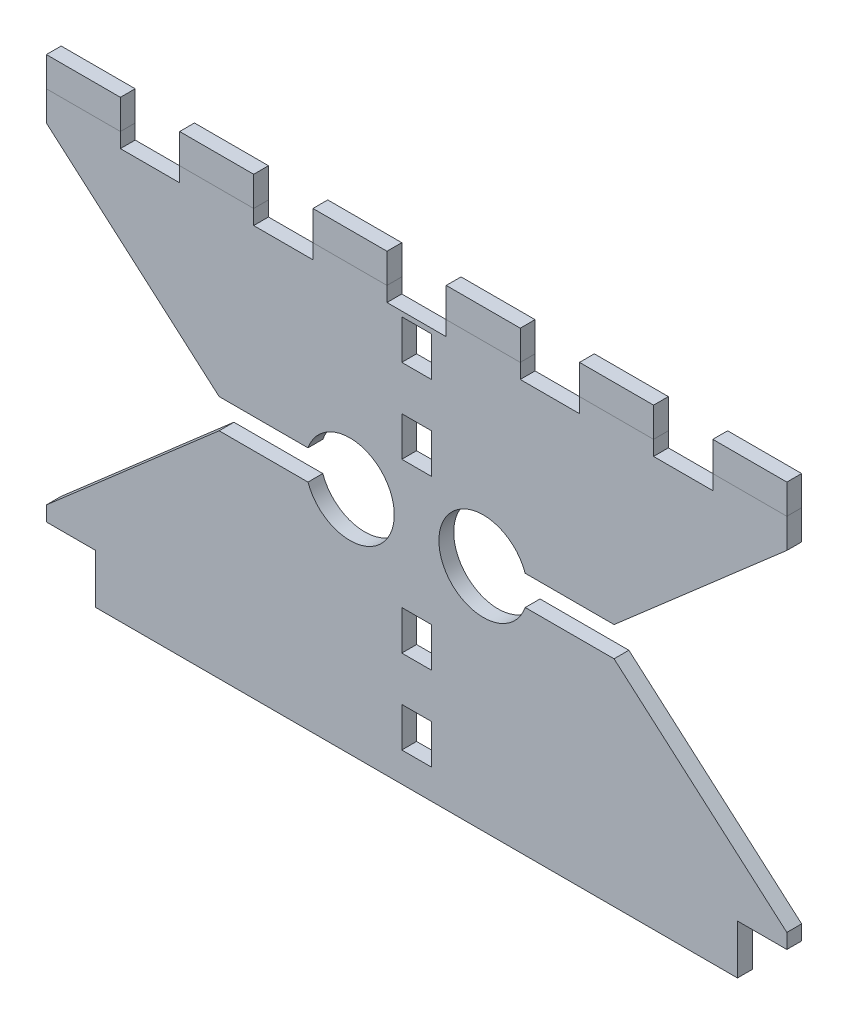
SolidWorks part; units mm, degrees
ref_plane "Plan de face" through (0, 0, 0) normal (0, 0, 1) x (1, 0, 0)
ref_plane "Plan de dessus" through (0, 0, 0) normal (0, 1, 0) x (1, 0, 0)
ref_plane "Plan de droite" through (0, 0, 0) normal (1, 0, 0) x (0, 0, -1)
sketch "Esquisse1" plane through (0, 0, 0) normal (0, 0, 1) x (1, 0, 0)
  line L0 (-89.4757, 0.6185) -> (-89.4757, 83.6185) construction
  line L1 (-164.4757, 47.1185) -> (-14.4757, 47.1185) construction
  line L2 (-164.4757, 80.6185) -> (-129.4757, 50.1185)
  line L3 (-164.4757, 13.6185) -> (-129.4757, 44.1185)
  line L4 (-129.4757, 50.1185) -> (-111.4757, 50.1185)
  line L5 (-129.4757, 44.1185) -> (-111.4757, 44.1185)
  line L6 (-14.4757, 13.6185) -> (-49.4757, 44.1185)
  line L7 (-49.4757, 44.1185) -> (-67.4757, 44.1185)
  line L8 (-49.4757, 50.1185) -> (-67.4757, 50.1185)
  line L9 (-14.4757, 80.6185) -> (-49.4757, 50.1185)
  line L10 (-164.4757, 13.6185) -> (-164.4757, 10.6185)
  line L11 (-164.4757, 10.6185) -> (-154.4757, 10.6185)
  line L12 (-154.4757, 10.6185) -> (-154.4757, 0.6185)
  line L13 (-154.4757, 0.6185) -> (-24.4757, 0.6185)
  line L14 (-24.4757, 0.6185) -> (-24.4757, 10.6185)
  line L15 (-24.4757, 10.6185) -> (-14.4757, 10.6185)
  line L16 (-14.4757, 10.6185) -> (-14.4757, 13.6185)
  line L17 (-14.4757, 80.6185) -> (-14.4757, 83.6185)
  line L18 (-14.4757, 83.6185) -> (-164.4757, 83.6185)
  line L19 (-164.4757, 83.6185) -> (-164.4757, 80.6185)
  circle A0 centre (-102.9904, 47.1185) radius 9
  circle A1 centre (-75.961, 47.1185) radius 9
  point P4 (-164.4757, 80.6185)
  dimension "D2" = 18
  dimension "D9" = 130
  dimension "D1" = 3
  dimension "D3" = 18
  dimension "D4" = 83
  dimension "D5" = 10
  dimension "D6" = 10
  dimension "D7" = 3
  dimension "D8" = 3
  dimension "D10" = 61.4853
  dimension "D11" = 46.5
  dimension "D12" = 65
extrude "Boss.-Extru.1" add sketch "Esquisse1" along normal blind 3 contours L7 A1 L8 L9 L17 L18 L19 L2 L4 A0 L5 L3 L10 L11 L12 L13 L14 L15 L16 L6
sketch "Esquisse2" plane through (0, 0, 3) normal (0, 0, 1) x (1, 0, 0)
  line L0 (-14.4757, 83.6185) -> (-164.4757, 83.6185) construction
  line L1 (-164.4757, 83.6185) -> (-149.4757, 83.6185)
  line L2 (-164.4757, 83.6185) -> (-164.4757, 86.6185)
  line L3 (-164.4757, 86.6185) -> (-149.4757, 86.6185)
  line L4 (-149.4757, 83.6185) -> (-149.4757, 86.6185)
  line L5 (-137.4757, 83.6185) -> (-122.4757, 83.6185)
  line L6 (-137.4757, 83.6185) -> (-137.4757, 86.6185)
  line L7 (-137.4757, 86.6185) -> (-122.4757, 86.6185)
  line L8 (-122.4757, 83.6185) -> (-122.4757, 86.6185)
  line L9 (-149.4757, 86.6185) -> (-137.4757, 86.6185)
  line L10 (-110.4757, 83.6185) -> (-95.4757, 83.6185)
  line L11 (-110.4757, 83.6185) -> (-110.4757, 86.6185)
  line L12 (-110.4757, 86.6185) -> (-95.4757, 86.6185)
  line L13 (-95.4757, 83.6185) -> (-95.4757, 86.6185)
  line L14 (-83.4757, 83.6185) -> (-68.4757, 83.6185)
  line L15 (-83.4757, 83.6185) -> (-83.4757, 86.6185)
  line L16 (-83.4757, 86.6185) -> (-68.4757, 86.6185)
  line L17 (-68.4757, 83.6185) -> (-68.4757, 86.6185)
  line L18 (-56.4757, 83.6185) -> (-41.4757, 83.6185)
  line L19 (-56.4757, 83.6185) -> (-56.4757, 86.6185)
  line L20 (-56.4757, 86.6185) -> (-41.4757, 86.6185)
  line L21 (-41.4757, 83.6185) -> (-41.4757, 86.6185)
  line L22 (-14.4757, 83.6185) -> (-29.4757, 83.6185)
  line L23 (-14.4757, 83.6185) -> (-14.4757, 86.6185)
  line L24 (-14.4757, 86.6185) -> (-29.4757, 86.6185)
  line L25 (-29.4757, 83.6185) -> (-29.4757, 86.6185)
  line L26 (-122.4757, 86.6185) -> (-110.4757, 86.6185)
  line L27 (-95.4757, 86.6185) -> (-83.4757, 86.6185)
  line L28 (-68.4757, 86.6185) -> (-56.4757, 86.6185)
  line L29 (-41.4757, 86.6185) -> (-29.4757, 86.6185)
  line M6 (-14.4757, 83.6185) -> (-164.4757, 83.6185)
  dimension "D1" = 15
  dimension "D2" = 3
extrude "Boss.-Extru.2" add sketch "Esquisse2" against normal blind 3 contours L4 L3 L2 M6 | L8 L7 L6 M6 | L13 L12 L11 M6 | L17 L16 L15 M6 | L21 L20 L19 M6 | L25 L23 L24 M6
sketch "Esquisse3" plane through (0, 0, 3) normal (0, 0, 1) x (1, 0, 0)
  line L1 (-164.4757, 86.6185) -> (-149.4757, 86.6185)
  line L2 (-164.4757, 86.6185) -> (-164.4757, 92.6185)
  line L3 (-164.4757, 92.6185) -> (-149.4757, 92.6185)
  line L4 (-149.4757, 86.6185) -> (-149.4757, 92.6185)
  line L5 (-137.4757, 86.6185) -> (-122.4757, 86.6185)
  line L6 (-137.4757, 86.6185) -> (-137.4757, 92.6185)
  line L7 (-137.4757, 92.6185) -> (-122.4757, 92.6185)
  line L8 (-122.4757, 86.6185) -> (-122.4757, 92.6185)
  line L9 (-110.4757, 86.6185) -> (-95.4757, 86.6185)
  line L10 (-110.4757, 86.6185) -> (-110.4757, 92.6185)
  line L11 (-110.4757, 92.6185) -> (-95.4757, 92.6185)
  line L12 (-95.4757, 86.6185) -> (-95.4757, 92.6185)
  line L13 (-83.4757, 86.6185) -> (-68.4757, 86.6185)
  line L14 (-83.4757, 86.6185) -> (-83.4757, 92.6185)
  line L15 (-83.4757, 92.6185) -> (-68.4757, 92.6185)
  line L16 (-68.4757, 86.6185) -> (-68.4757, 92.6185)
  line L17 (-56.4757, 86.6185) -> (-41.4757, 86.6185)
  line L18 (-56.4757, 86.6185) -> (-56.4757, 92.6185)
  line L19 (-56.4757, 92.6185) -> (-41.4757, 92.6185)
  line L20 (-41.4757, 86.6185) -> (-41.4757, 92.6185)
  line L21 (-29.4757, 86.6185) -> (-14.4757, 86.6185)
  line L22 (-29.4757, 86.6185) -> (-29.4757, 92.6185)
  line L23 (-29.4757, 92.6185) -> (-14.4757, 92.6185)
  line L24 (-14.4757, 86.6185) -> (-14.4757, 92.6185)
  dimension "D1" = 6
extrude "Boss.-Extru.3" add sketch "Esquisse3" against normal blind 3 separate body
sketch "Esquisse4" plane through (0, 0, 3) normal (0, 0, 1) x (1, 0, 0)
  line L1 (-92.4757, 82.6185) -> (-86.4757, 82.6185)
  line L2 (-92.4757, 82.6185) -> (-92.4757, 74.6185)
  line L3 (-92.4757, 74.6185) -> (-86.4757, 74.6185)
  line L4 (-86.4757, 82.6185) -> (-86.4757, 74.6185)
  line L5 (-92.4757, 65.6185) -> (-86.4757, 65.6185)
  line L6 (-92.4757, 65.6185) -> (-92.4757, 57.6185)
  line L7 (-92.4757, 57.6185) -> (-86.4757, 57.6185)
  line L8 (-86.4757, 65.6185) -> (-86.4757, 57.6185)
  line L9 (-92.4757, 31.6185) -> (-86.4757, 31.6185)
  line L10 (-92.4757, 31.6185) -> (-92.4757, 23.6185)
  line L11 (-92.4757, 23.6185) -> (-86.4757, 23.6185)
  line L12 (-86.4757, 31.6185) -> (-86.4757, 23.6185)
  line L13 (-92.4757, 14.6185) -> (-86.4757, 14.6185)
  line L14 (-92.4757, 14.6185) -> (-92.4757, 6.6185)
  line L15 (-92.4757, 6.6185) -> (-86.4757, 6.6185)
  line L16 (-86.4757, 14.6185) -> (-86.4757, 6.6185)
extrude "Enlèv. mat.-Extru.1" cut sketch "Esquisse4" against normal blind 3
